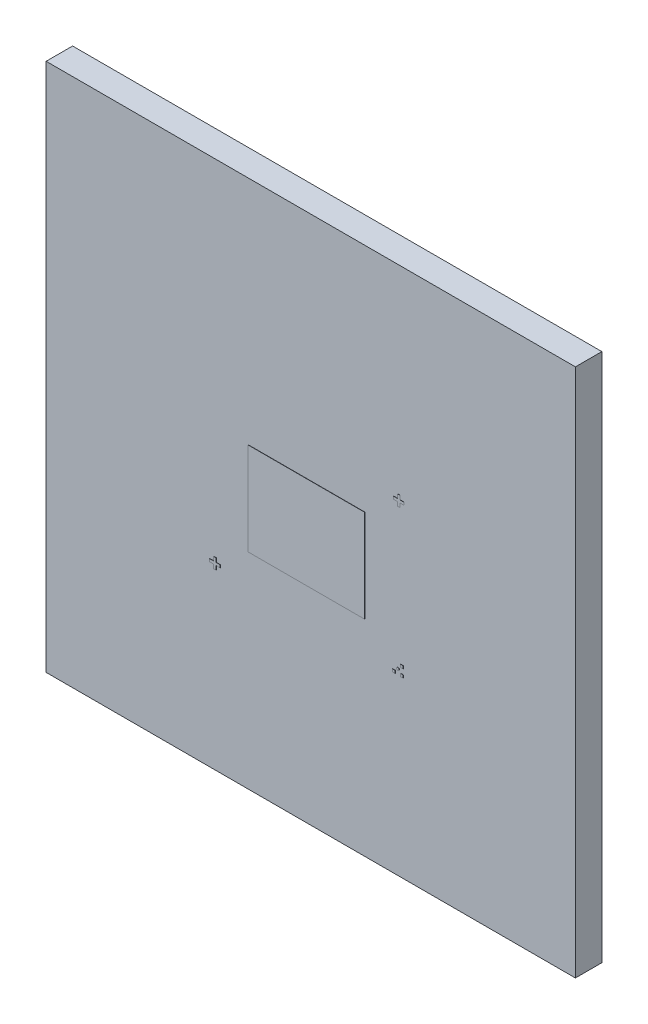
SolidWorks part; units mm, degrees
ref_plane "Front Plane" through (0, 0, 0) normal (0, 0, 1) x (1, 0, 0)
ref_plane "Top Plane" through (0, 0, 0) normal (0, 1, 0) x (1, 0, 0)
ref_plane "Right Plane" through (0, 0, 0) normal (1, 0, 0) x (0, 0, -1)
sketch "Sketch1" plane through (0, 0, 0) normal (0, 0, 1) x (1, 0, 0)
  line L1 (0, 0) -> (20, 0)
  line L2 (0, 0) -> (0, 20)
  line L3 (0, 20) -> (20, 20)
  line L4 (20, 0) -> (20, 20)
  dimension "D1" = 20
  dimension "D2" = 20
extrude "Boss-Extrude1" add sketch "Sketch1" along normal blind 1
sketch "Sketch2" plane through (0, 0, 1) normal (0, 0, 1) x (1, 0, 0)
  line L0 (4.9506, 13.4106) -> (14.6851, 5.6673) construction
  line L1 (7.6421, 11.2696) -> (12.0421, 11.2696) construction
  line L2 (6.335, 6.9696) -> (6.335, 6.8196)
  line L3 (6.335, 6.8196) -> (6.185, 6.8196)
  line L4 (6.185, 6.8196) -> (6.185, 6.7196)
  line L5 (5.8518, 6.7696) -> (14.9011, 6.7696) construction
  line L6 (6.385, 6.895) -> (6.385, 5.9885) construction
  line L7 (6.335, 6.9696) -> (6.435, 6.9696)
  line L8 (6.585, 6.8196) -> (6.585, 6.7196)
  line L9 (6.435, 6.8196) -> (6.585, 6.8196)
  line L10 (6.435, 6.9696) -> (6.435, 6.8196)
  line L11 (6.435, 6.5696) -> (6.435, 6.7196)
  line L12 (6.435, 6.7196) -> (6.585, 6.7196)
  line L13 (6.335, 6.5696) -> (6.435, 6.5696)
  line L14 (6.335, 6.7196) -> (6.185, 6.7196)
  line L15 (6.335, 6.5696) -> (6.335, 6.7196)
  line L16 (7.6421, 11.2696) -> (7.6421, 7.7696) construction
  line L17 (7.6421, 7.7696) -> (12.0421, 7.7696) construction
  line L18 (12.0421, 11.2696) -> (12.0421, 7.7696) construction
  line L19 (14.1147, 12.9182) -> (4.3843, 5.1782) construction
  line L20 (13.8989, 7.3693) -> (13.0271, 6.4974) construction
  line L21 (13.3993, 6.971) -> (13.4993, 6.971)
  line L22 (13.3993, 6.971) -> (13.3993, 6.8683)
  line L23 (13.3993, 6.8683) -> (13.4993, 6.8683)
  line L24 (13.4993, 6.971) -> (13.4993, 6.8683)
  line L25 (13.3993, 6.671) -> (13.4993, 6.671)
  line L26 (13.3993, 6.671) -> (13.3993, 6.5683)
  line L27 (13.3993, 6.5683) -> (13.4993, 6.5683)
  line L28 (13.4993, 6.671) -> (13.4993, 6.5683)
  line L29 (13.0993, 6.671) -> (13.1993, 6.671)
  line L30 (13.0993, 6.671) -> (13.0993, 6.5683)
  line L31 (13.0993, 6.5683) -> (13.1993, 6.5683)
  line L32 (13.1993, 6.671) -> (13.1993, 6.5683)
  line L33 (13.0464, 7.0225) -> (13.8816, 6.1873) construction
  line L34 (13.3993, 6.971) -> (13.4993, 6.8683) construction
  line L35 (13.3993, 6.5683) -> (13.4993, 6.671) construction
  line L36 (13.1993, 6.5683) -> (13.0993, 6.671) construction
  line L37 (13.2788, 12.4896) -> (13.2788, 12.3396)
  line L38 (13.3788, 12.3396) -> (13.5288, 12.3396)
  line L39 (13.2788, 12.2396) -> (13.1288, 12.2396)
  line L40 (13.1288, 12.3396) -> (13.1288, 12.2396)
  line L41 (13.2788, 12.0896) -> (13.3788, 12.0896)
  line L42 (13.2788, 12.4896) -> (13.3788, 12.4896)
  line L43 (13.3788, 12.2396) -> (13.5288, 12.2396)
  line L44 (13.2788, 12.0896) -> (13.2788, 12.2396)
  line L45 (13.3788, 12.0896) -> (13.3788, 12.2396)
  line L46 (13.3788, 12.4896) -> (13.3788, 12.3396)
  line L47 (13.2788, 12.3396) -> (13.1288, 12.3396)
  line L48 (13.5288, 12.3396) -> (13.5288, 12.2396)
  circle A0 centre (13.2993, 6.7696) radius 0.05
  point P2 (6.385, 6.7696)
  point P3 (13.2993, 12.2696)
  point P18 (6.385, 6.9696)
  point P21 (6.385, 6.5696)
  point P25 (6.585, 6.7696)
  point P27 (6.185, 6.7696)
  point P31 (6.385, 6.7696)
  point P49 (13.4493, 6.9196)
  point P52 (13.1493, 6.6196)
  point P53 (13.4493, 6.6196)
  point P58 (13.3288, 12.4896)
  point P61 (13.3288, 12.0896)
  point P65 (13.5288, 12.2896)
  point P67 (13.1288, 12.2896)
  point P68 (13.3288, 12.2896)
  point P69 (0, 0)
  point P70 (0, 0)
  dimension "D7" = 0.1
  dimension "D1" = 0.05
  dimension "D2" = 0.2
  dimension "D3" = 0.05
  dimension "D4" = 0.2
  dimension "D5" = 4.4
  dimension "D6" = 3.5
  dimension "D8" = 0.1
  dimension "D9" = 0.1027
  dimension "D10" = 45
  dimension "D11" = 45
  dimension "D12" = 0.2
  dimension "D13" = 0.05
  dimension "D14" = 1
extrude "Boss-Extrude2" add sketch "Sketch2" along normal blind 0.01 separate body
sketch "Sketch3" plane through (0, 0, 1) normal (0, 0, 1) x (1, 0, 0)
  line L1 (7.6421, 11.2696) -> (12.0421, 11.2696)
  line L2 (7.6421, 11.2696) -> (7.6421, 7.7696)
  line L3 (7.6421, 7.7696) -> (12.0421, 7.7696)
  line L4 (12.0421, 11.2696) -> (12.0421, 7.7696)
extrude "Boss-Extrude3" add sketch "Sketch3" along normal blind 0.01 separate body
